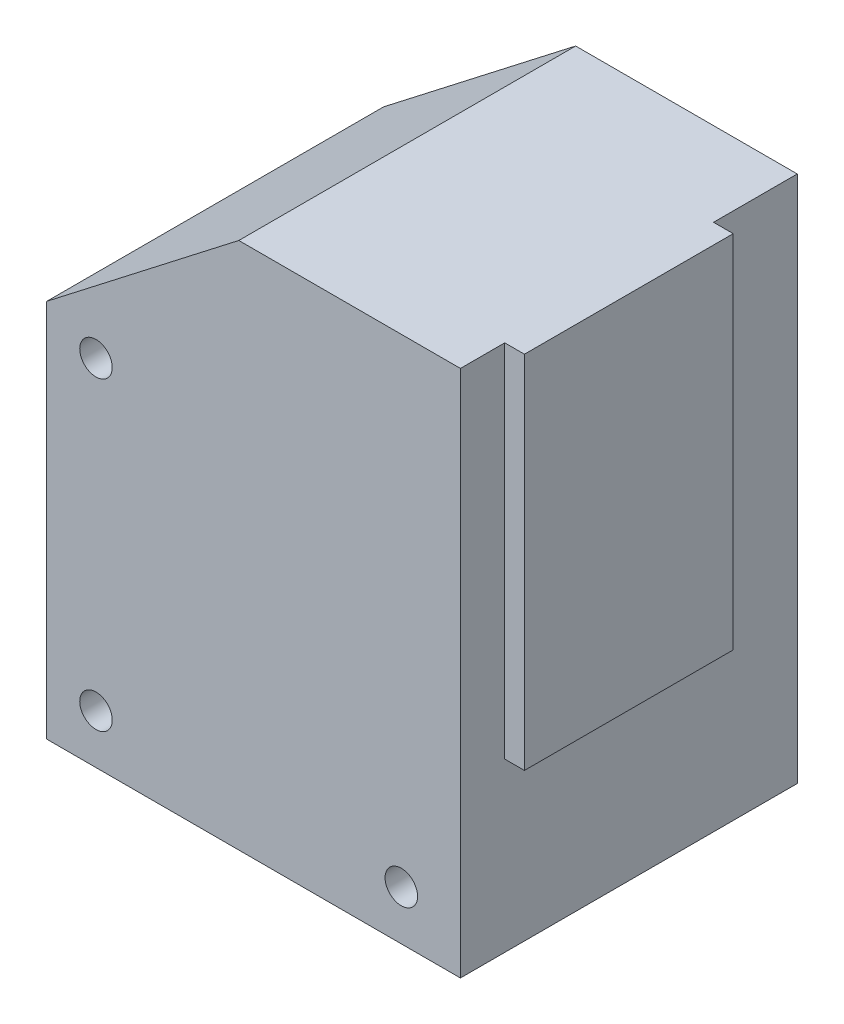
SolidWorks part; units mm, degrees
ref_plane "Front Plane" through (0, 0, 0) normal (0, 0, 1) x (1, 0, 0)
ref_plane "Top Plane" through (0, 0, 0) normal (0, 1, 0) x (1, 0, 0)
ref_plane "Right Plane" through (0, 0, 0) normal (1, 0, 0) x (0, 0, -1)
sketch "Sketch1" plane through (0, 0, 0) normal (0, 0, 1) x (1, 0, 0)
  line L0 (0, 38.5) -> (19.5, 53.6)
  line L1 (0, 0) -> (42, 0)
  line L2 (0, 0) -> (0, 38.5)
  line L3 (19.5, 53.6) -> (42, 53.6)
  line L4 (42, 0) -> (42, 53.6)
  dimension "D1" = 53.6
  dimension "D2" = 42
  dimension "D3" = 22.5
  dimension "D4" = 38.5
extrude "Boss-Extrude1" add sketch "Sketch1" along normal blind 34.2
sketch "Sketch2" plane through (0, 0, 0) normal (0, -1, 0) x (1, 0, 0)
  line L0 (42, 34.2) -> (42, 0) construction
  line L1 (0, 34.2) -> (42, 34.2) construction
  circle A0 centre (26, 23.7) radius 8
  dimension "D3" = 16
  dimension "D1" = 16
  dimension "D2" = 10.5
extrude "Cut-Extrude1" cut sketch "Sketch2" against normal blind 10
sketch "Sketch3" plane through (42, 0, 0) normal (1, 0, 0) x (0, 0, -1)
  line L0 (-34.2, 53.6) -> (0, 53.6) construction
  line L1 (-29.7, 53.6) -> (-8.5, 53.6)
  line L2 (-29.7, 53.6) -> (-29.7, 17)
  line L3 (-29.7, 17) -> (-8.5, 17)
  line L4 (-8.5, 53.6) -> (-8.5, 17)
  line L5 (-34.2, 0) -> (-34.2, 53.6) construction
  line L6 (0, 0) -> (0, 53.6) construction
  line L7 (-34.2, 0) -> (0, 0) construction
  dimension "D1" = 4.5
  dimension "D2" = 8.5
  dimension "D3" = 17
extrude "Boss-Extrude2" add sketch "Sketch3" along normal blind 2
sketch "Sketch4" plane through (0, 0, 0) normal (0, 0, -1) x (-1, 0, 0)
  line L0 (-42, 2) -> (-40, 0)
  line L1 (-42, 0) -> (-42, 53.6) construction
  line L2 (0, 0) -> (-42, 0) construction
  line L3 (-40, 0) -> (-42, 0)
  line L4 (-42, 0) -> (-42, 2)
  line L5 (0, 2) -> (-2, 0)
  line L6 (0, 38.5) -> (0, 0) construction
  line L7 (-2, 0) -> (0, 0)
  line L8 (0, 0) -> (0, 2)
  dimension "D1" = 45
  dimension "D2" = 2
  dimension "D3" = 2
extrude "Cut-Extrude3" [suppressed] cut sketch "Sketch4" against normal through all
fillet "Fillet1" [suppressed] radius 1
sketch "Sketch5" plane through (0, 0, 0) normal (0, 0, -1) x (-1, 0, 0)
  line L1 (-36, 5) -> (-5, 5) construction
  line L2 (-36, 5) -> (-36, 36) construction
  line L3 (-36, 36) -> (-5, 36) construction
  line L4 (-5, 5) -> (-5, 36) construction
  line L5 (0, 0) -> (-42, 0) construction
  line L6 (0, 38.5) -> (0, 0) construction
  circle A0 centre (-36, 5) radius 1.65
  circle A1 centre (-5, 5) radius 1.65
  circle A2 centre (-5, 36) radius 1.65
  dimension "D3" = 3.3
  dimension "D1" = 31
  dimension "D2" = 31
  dimension "D4" = 5
  dimension "D5" = 5
extrude "Cut-Extrude4" cut sketch "Sketch5" against normal through all
